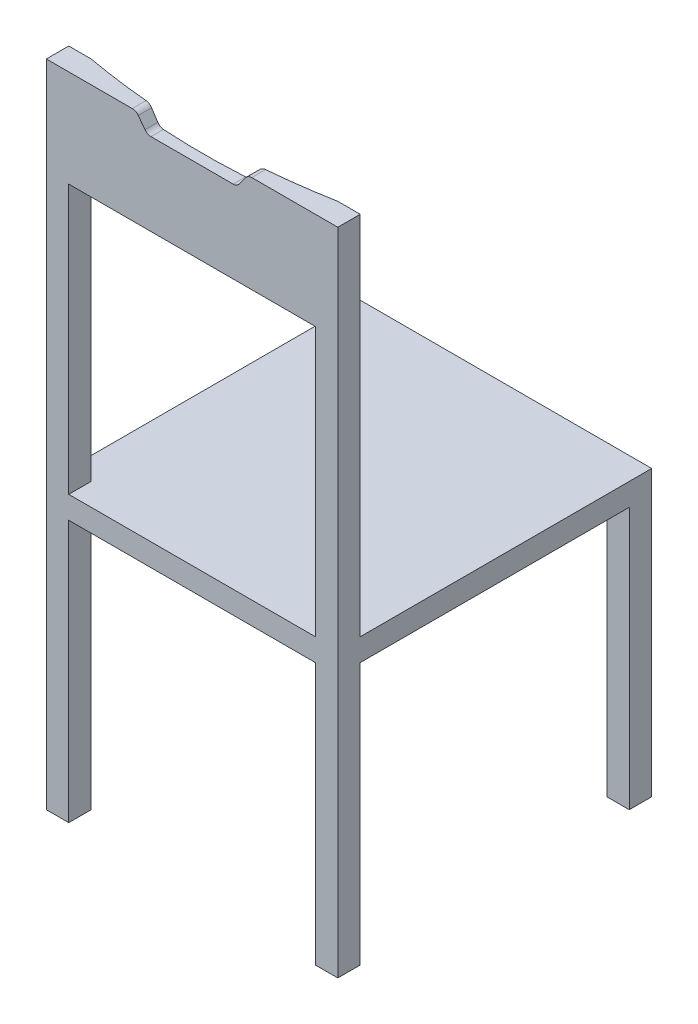
SolidWorks part; units mm, degrees
material "Teak"
ref_plane "Front Plane" through (0, 0, 0) normal (0, 0, 1) x (1, 0, 0)
ref_plane "Top Plane" through (0, 0, 0) normal (0, 1, 0) x (1, 0, 0)
ref_plane "Right Plane" through (0, 0, 0) normal (1, 0, 0) x (0, 0, -1)
sketch "Sketch1" plane through (0, 0, 0) normal (0, 1, 0) x (1, 0, 0)
  line L1 (195, -210) -> (-195, -210) construction
  line L2 (195, -210) -> (195, 210) construction
  line L3 (195, 210) -> (-195, 210) construction
  line L4 (-195, -210) -> (-195, 210) construction
  line L5 (195, -210) -> (-195, 210) construction
  line L6 (195, 210) -> (-195, -210) construction
  point P0 (0, 0)
  dimension "D1" = 390
  dimension "D2" = 420
sketch "Sketch2" plane through (0, 0, 0) normal (0, 1, 0) x (1, 0, 0)
  line L0 (195, -210) -> (-195, -210) construction
  line L1 (-195, -210) -> (-165, -210)
  line L2 (-195, -210) -> (-195, -180)
  line L3 (-195, -180) -> (-165, -180)
  line L4 (-165, -210) -> (-165, -180)
  line L5 (-195, -210) -> (-165, -180) construction
  line L6 (-195, -180) -> (-165, -210) construction
  line L7 (195, -210) -> (165, -210)
  line L8 (195, -210) -> (195, -180)
  line L9 (195, -180) -> (165, -180)
  line L10 (165, -210) -> (165, -180)
  line L11 (195, -210) -> (165, -180) construction
  line L12 (195, -180) -> (165, -210) construction
  line L13 (-195, -210) -> (-195, 210) construction
  line L14 (195, -210) -> (195, 210) construction
  point P0 (-195, -195)
  point P6 (195, -195)
  dimension "D1" = 30
extrude "Boss-Extrude1" add sketch "Sketch2" along normal blind 489.54 and the other way blind 430
sketch "Sketch3" plane through (0, 0, 0) normal (0, 1, 0) x (1, 0, 0)
  line L0 (195, 210) -> (-195, 210) construction
  line L1 (-165, 180) -> (-195, 180)
  line L2 (-165, 180) -> (-165, 210)
  line L3 (-165, 210) -> (-195, 210)
  line L4 (-195, 180) -> (-195, 210)
  line L5 (-165, 180) -> (-195, 210) construction
  line L6 (-165, 210) -> (-195, 180) construction
  line L7 (195, 180) -> (165, 180)
  line L8 (195, 180) -> (195, 210)
  line L9 (195, 210) -> (165, 210)
  line L10 (165, 180) -> (165, 210)
  line L11 (195, 180) -> (165, 210) construction
  line L12 (195, 210) -> (165, 180) construction
  line L13 (-195, -210) -> (-195, 210) construction
  line L14 (195, -210) -> (195, 210) construction
  point P0 (-195, 195)
  point P6 (195, 195)
  dimension "D1" = 30
extrude "Boss-Extrude2" add sketch "Sketch3" against normal blind 430 separate body
sketch "Sketch4" plane through (0, 0, 0) normal (0, 1, 0) x (1, 0, 0)
  line L0 (-165, 210) -> (165, 210)
  line L1 (165, 210) -> (165, 180)
  line L2 (165, 180) -> (195, 180)
  line L3 (195, 180) -> (195, -180)
  line L4 (-195, -180) -> (-165, -180)
  line L5 (-195, -180) -> (-195, 180)
  line L6 (-195, 180) -> (-165, 180)
  line L7 (-165, 180) -> (-165, 210)
  line L8 (-165, -180) -> (-165, -210)
  line L9 (-165, -210) -> (165, -210)
  line L10 (165, -210) -> (165, -180)
  line L11 (165, -180) -> (195, -180)
extrude "Boss-Extrude3" add sketch "Sketch4" against normal blind 30
sketch "Sketch5" plane through (0, 489.54, 0) normal (0, 1, 0) x (1, 0, 0)
  line L0 (-165, -180) -> (-165, -210)
  line L1 (-165, -210) -> (165, -210)
  line L2 (165, -210) -> (165, -180)
  arc A0 (-165, -180) -> (165, -180) centre (0, 720) ccw
  point P9 (-165, -195)
  point P10 (0, -195)
extrude "Boss-Extrude4" add sketch "Sketch5" against normal blind 130
sketch "Sketch7" plane through (0, 0, 210) normal (0, 0, 1) x (1, 0, 0)
  line L0 (0, 359.54) -> (0, 489.54) construction
  line L2 (-165, 359.54) -> (165, 359.54) construction
  line L3 (-195, 489.54) -> (195, 489.54) construction
  line L4 (75, 489.54) -> (-75, 489.54)
  line L5 (-75, 489.54) -> (-63, 473.54)
  line L6 (-55, 469.54) -> (55, 469.54)
  line L7 (75, 489.54) -> (63, 473.54)
  line L8 (-195, 424.54) -> (195, 424.54) construction
  line L9 (195, -430) -> (195, 489.54) construction
  arc A0 (63, 473.54) -> (55, 469.54) centre (55, 479.54) cw
  arc A1 (-63, 473.54) -> (-55, 469.54) centre (-55, 479.54) ccw
  point P9 (0, 489.54)
  point P12 (0, 469.54)
  point P14 (60, 469.54)
  point P17 (-60, 469.54)
  point P23 (0, 424.54)
  dimension "D4" = 10
  dimension "D1" = 150
  dimension "D2" = 60
  dimension "D3" = 20
extrude "Cut-Extrude2" cut sketch "Sketch7" against normal up to next
fillet "Fillet1" radius 10 2 edges at (75, 489.54, 200.9605) (-75, 489.54, 200.9605)
sketch "Sketch8" plane through (0, 0, 210) normal (0, 0, 1) x (1, 0, 0)
  line L0 (195, -430) -> (195, 489.54) construction
  line L1 (-195, -430) -> (195, -430)
  line L2 (-195, -430) -> (-195, -380.46)
  line L3 (-195, -380.46) -> (195, -380.46)
  line L4 (195, -430) -> (195, -380.46)
  dimension "D1" = 49.54
extrude "Cut-Extrude3" cut sketch "Sketch8" against normal through all
